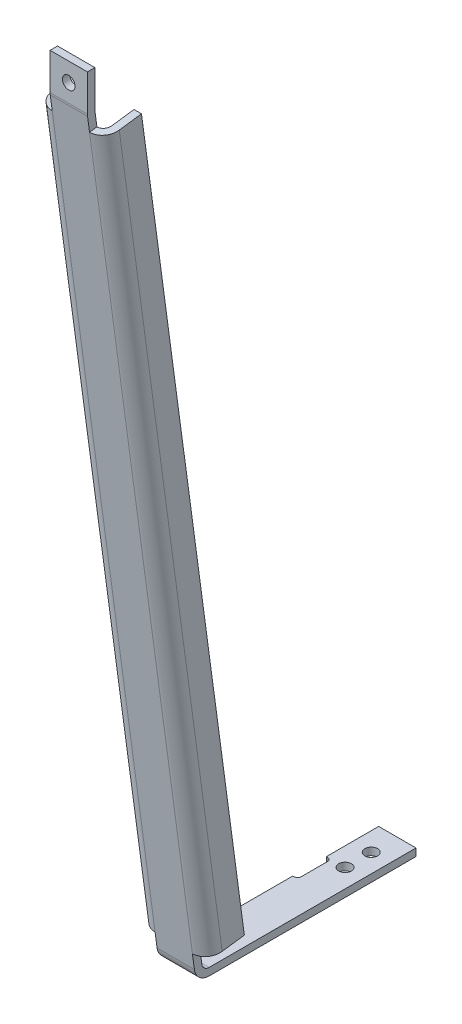
SolidWorks part; units mm, degrees
other "Roof Support Arm 2 Left"
ref_plane "Front Plane" through (0, 0, 0) normal (0, 0, 1) x (1, 0, 0)
ref_plane "Top Plane" through (0, 0, 0) normal (0, 1, 0) x (1, 0, 0)
ref_plane "Right Plane" through (0, 0, 0) normal (1, 0, 0) x (0, 0, -1)
sketch3d "Formed Web Section Sketch datum points"
  point P0 (-30, 0, 0)
  point P1 (-30, 10, 0)
  point P2 (-30, 0, 10)
ref_plane "Formed Web Section Sketch plane" through (-30, 0, 0) normal (1, 0, 0) x (0, 0, -1)
sketch "Formed Web Section Sketch" plane through (-30, 0, 0) normal (1, 0, 0) x (0, 0, -1)
  line L0 (-22, 64) -> (-77.3775, 64)
  line L1 (-81.3416, 67.4653) -> (-109.9641, 279.6667)
  line L2 (-110, 280.2014) -> (-110, 290)
  line L3 (-110, 290) -> (-108, 290)
  line L4 (-108, 290) -> (-108, 280.2014)
  line L5 (-107.9821, 279.9341) -> (-79.3595, 67.7327)
  line L6 (-77.3775, 66) -> (-22, 66)
  line L7 (-22, 66) -> (-22, 64)
  arc A0 (-81.3416, 67.4653) -> (-77.3775, 64) centre (-77.3775, 68) ccw
  arc A1 (-110, 280.2014) -> (-109.9641, 279.6667) centre (-106, 280.2014) ccw
  arc A2 (-108, 280.2014) -> (-107.9821, 279.9341) centre (-106, 280.2014) ccw
  arc A3 (-79.3595, 67.7327) -> (-77.3775, 66) centre (-77.3775, 68) ccw
extrude "Formed Web" add sketch "Formed Web Section Sketch" along normal blind 10 separate body
sketch3d "Edge Lip Sketch datum points"
  point P0 (-25, 71.5631, 80.8853)
  point P1 (-15, 71.5631, 80.8853)
  point P2 (-25, 70.2264, 90.7955)
ref_plane "Edge Lip Sketch plane" through (0, 80.9995, 10.9255) normal (0, -0.991, -0.1337) x (-1, 0, 0)
sketch "Edge Lip Sketch" plane through (0, 80.9995, 10.9255) normal (0, -0.991, -0.1337) x (-1, 0, 0)
  line L0 (34, -67.5933) -> (34, -61.5933)
  line L1 (34, -61.5933) -> (32, -61.5933)
  line L2 (32, -61.5933) -> (32, -67.5933)
  line L3 (30, -69.5933) -> (29.9, -69.5933)
  line L4 (29.9, -69.5933) -> (29.9, -71.5933)
  line L5 (29.9, -71.5933) -> (30, -71.5933)
  line L6 (16, -67.5933) -> (16, -61.5933)
  line L7 (16, -61.5933) -> (18, -61.5933)
  line L8 (18, -61.5933) -> (18, -67.5933)
  line L9 (20, -69.5933) -> (20.1, -69.5933)
  line L10 (20.1, -69.5933) -> (20.1, -71.5933)
  line L11 (20.1, -71.5933) -> (20, -71.5933)
  arc A0 (30, -71.5933) -> (34, -67.5933) centre (30, -67.5933) ccw
  arc A1 (30, -69.5933) -> (32, -67.5933) centre (30, -67.5933) ccw
  arc A2 (16, -67.5933) -> (20, -71.5933) centre (20, -67.5933) ccw
  arc A3 (18, -67.5933) -> (20, -69.5933) centre (20, -67.5933) ccw
extrude "Edge Stiffening Lips" add sketch "Edge Lip Sketch" against normal blind 206.1231
sketch3d "Wall Mount Hole Sketch datum points"
  point P0 (0, 63.8, 0)
  point P1 (10, 63.8, 0)
  point P2 (0, 63.8, 10)
ref_plane "Wall Mount Hole Sketch plane" through (0, 63.8, 0) normal (0, -1, 0) x (-1, 0, 0)
sketch "Wall Mount Hole Sketch" plane through (0, 63.8, 0) normal (0, -1, 0) x (-1, 0, 0)
  circle A0 centre (25, -29) radius 1.7
  circle A1 centre (25, -36) radius 1.7
extrude "Wall Mount Holes" cut sketch "Wall Mount Hole Sketch" against normal blind 2.4
sketch3d "Cover Mount Hole Sketch datum points"
  point P0 (0, 0, 107.8)
  point P1 (10, 0, 107.8)
  point P2 (0, 10, 107.8)
ref_plane "Cover Mount Hole Sketch plane" through (0, 0, 107.8) normal (0, 0, 1) x (1, 0, 0)
sketch "Cover Mount Hole Sketch" plane through (0, 0, 107.8) normal (0, 0, 1) x (1, 0, 0)
  circle A0 centre (-25, 285) radius 1.7
extrude "Cover Mount Hole" cut sketch "Cover Mount Hole Sketch" along normal blind 2.4
sketch3d "Frame Mount Relief Sketch datum points"
  point P0 (0, 63.8, 0)
  point P1 (10, 63.8, 0)
  point P2 (0, 63.8, 10)
ref_plane "Frame Mount Relief Sketch plane" through (0, 63.8, 0) normal (0, -1, 0) x (-1, 0, 0)
sketch "Frame Mount Relief Sketch" plane through (0, 63.8, 0) normal (0, -1, 0) x (-1, 0, 0)
  line L0 (30, -36) -> (29.7, -36)
  line L1 (28.7, -37) -> (28.7, -44)
  line L2 (29.7, -45) -> (30, -45)
  line L3 (31, -44) -> (31, -37)
  arc A0 (31, -37) -> (30, -36) centre (30, -37) ccw
  arc A1 (29.7, -36) -> (28.7, -37) centre (29.7, -37) ccw
  arc A2 (28.7, -44) -> (29.7, -45) centre (29.7, -44) ccw
  arc A3 (30, -45) -> (31, -44) centre (30, -44) ccw
extrude "Frame Mount Relief" cut sketch "Frame Mount Relief Sketch" against normal blind 2.4
